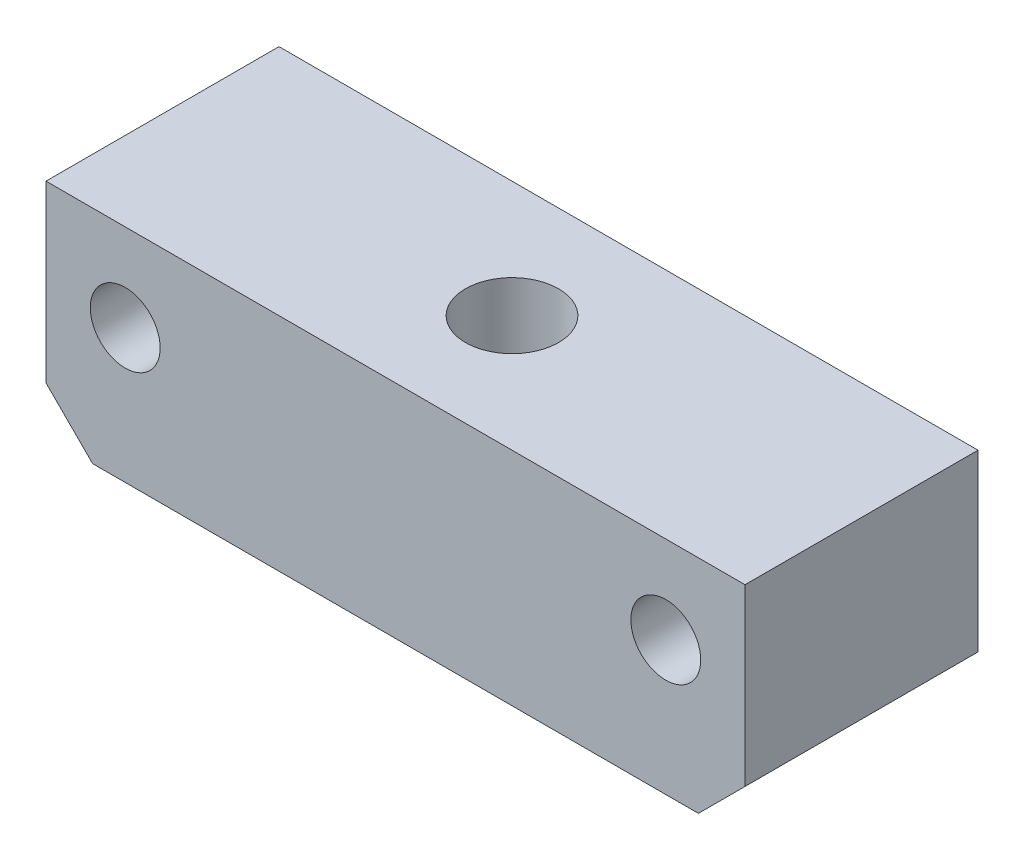
SolidWorks part; units mm, degrees
ref_plane "Front Plane" through (0, 0, 0) normal (0, 0, 1) x (1, 0, 0)
ref_plane "Top Plane" through (0, 0, 0) normal (0, 1, 0) x (1, 0, 0)
ref_plane "Right Plane" through (0, 0, 0) normal (1, 0, 0) x (0, 0, -1)
sketch "Sketch1" plane through (0, 0, 0) normal (0, 0, 1) x (1, 0, 0)
  line L0 (-15, 2.5) -> (-15, -5)
  line L1 (-15, -5) -> (-13, -7)
  line L2 (-13, -7) -> (13, -7)
  line L3 (13, -7) -> (15, -5)
  line L4 (15, -5) -> (15, 2.5)
  line L5 (15, 2.5) -> (-15, 2.5)
  circle A0 centre (11.6, -1.25) radius 1.5 construction
  circle A1 centre (-11.6, -1.25) radius 1.5 construction
  circle A2 centre (11.6, -1.25) radius 1.5
  circle A3 centre (-11.6, -1.25) radius 1.5
extrude "Boss-Extrude1" add sketch "Sketch1" along normal blind 10
hole_wizard "CSK for M4 SFHCS1" positions "Sketch8" profile "Sketch9" countersink size "M4" standard "ANSI Metric"
sketch "Sketch8" plane through (1278.2473, -7, -931.083) normal (0, -1, 0) x (1, 0, 0)
  point P0 (-1278.2473, 936.083)
sketch "Sketch9" plane through (0, -7, 5) normal (1, 0, 0) x (0, 0, -1)
  line L0 (0, 0) -> (0, 20.2017)
  line L1 (0, 20.2017) -> (2, 19)
  line L2 (2, 19) -> (2, 1.95)
  line L3 (2, 1.95) -> (3.95, 0)
  line L4 (3.95, 0) -> (0, 0)
  line L5 (-2, 1.95) -> (-3.95, 0) construction
  line L6 (0, 20.2017) -> (-2, 19) construction
  line L7 (0, -6.35) -> (0, 107.95) construction
  dimension "Hole Dia." = 4
  dimension "Hole Depth" = 19
  dimension "Near C'Sink Dia." = 7.9
  dimension "Near C'Sink Angle" = 90
  dimension "Drill Angle" = 118
hole_wizard "CSK for M3 SFHCS1" positions "Sketch4" profile "Sketch5" countersink size "M3" standard "ANSI Metric"
sketch "Sketch4" plane through (-1278.2473, -657.683, 10) normal (0, 0, 1) x (0, 1, 0)
  point P0 (656.433, -1266.6473)
  point P3 (656.433, -1289.8473)
  point P6 (734.933, -1289.8473)
  point P9 (734.933, -1266.6473)
sketch "Sketch5" plane through (-11.6, -1.25, 10) normal (1, 0, 0) x (0, -1, 0)
  line L0 (0, 0) -> (0, 5.9013)
  line L1 (0, 5.9013) -> (1.5, 5)
  line L2 (1.5, 5) -> (1.5, 1.6)
  line L3 (1.5, 1.6) -> (3.1, 0)
  line L4 (3.1, 0) -> (0, 0)
  line L5 (-1.5, 1.6) -> (-3.1, 0) construction
  line L6 (0, 5.9013) -> (-1.5, 5) construction
  line L7 (0, -6.35) -> (0, 107.95) construction
  dimension "Hole Dia." = 3
  dimension "Hole Depth" = 5
  dimension "Near C'Sink Dia." = 6.2
  dimension "Near C'Sink Angle" = 90
  dimension "Drill Angle" = 118
hole_wizard "CSK for M3 SFHCS2" positions "Sketch6" profile "Sketch7" countersink size "M3" standard "ANSI Metric"
sketch "Sketch6" plane through (1278.2473, 733.683, 10) normal (0, 0, 1) x (0, -1, 0)
  point P0 (656.433, -1266.6473)
  point P3 (656.433, -1289.8473)
  point P6 (734.933, -1289.8473)
  point P9 (734.933, -1266.6473)
sketch "Sketch7" plane through (11.6, 77.25, 10) normal (1, 0, 0) x (0, -1, 0)
  line L0 (0, 0) -> (0, 5.9013)
  line L1 (0, 5.9013) -> (1.5, 5)
  line L2 (1.5, 5) -> (1.5, 1.6)
  line L3 (1.5, 1.6) -> (3.1, 0)
  line L4 (3.1, 0) -> (0, 0)
  line L5 (-1.5, 1.6) -> (-3.1, 0) construction
  line L6 (0, 5.9013) -> (-1.5, 5) construction
  line L7 (0, -6.35) -> (0, 107.95) construction
  dimension "Hole Dia." = 3
  dimension "Hole Depth" = 5
  dimension "Near C'Sink Dia." = 6.2
  dimension "Near C'Sink Angle" = 90
  dimension "Drill Angle" = 118
